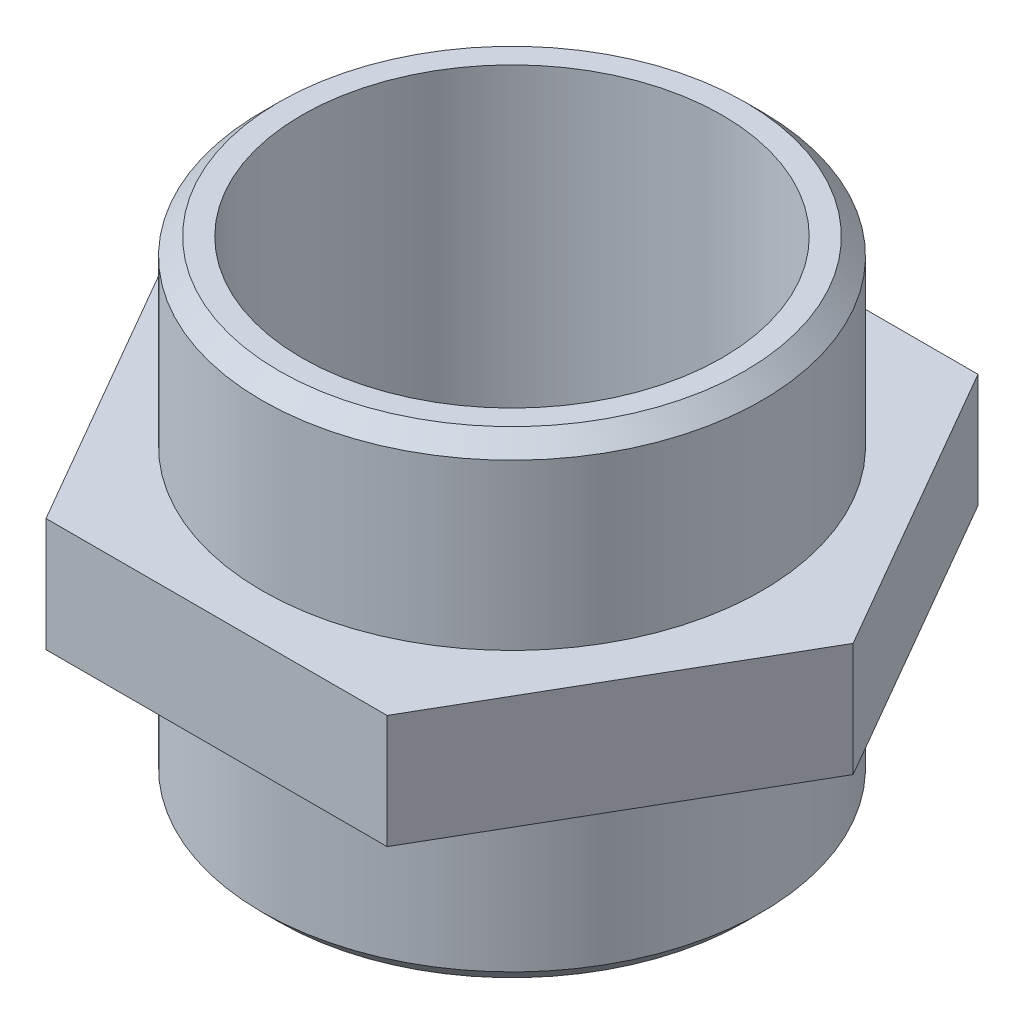
SolidWorks part; units mm, degrees
material "Brass"
ref_plane "Front Plane" through (0, 0, 0) normal (0, 0, 1) x (1, 0, 0)
ref_plane "Top Plane" through (0, 0, 0) normal (0, 1, 0) x (1, 0, 0)
ref_plane "Right Plane" through (0, 0, 0) normal (1, 0, 0) x (0, 0, -1)
sketch "Sketch1" plane through (0, 0, 0) normal (0, 1, 0) x (1, 0, 0)
  line L1 (15.0111, -26) -> (30.0222, 0)
  line L2 (30.0222, 0) -> (15.0111, 26)
  line L3 (15.0111, 26) -> (-15.0111, 26)
  line L4 (-15.0111, 26) -> (-30.0222, 0)
  line L5 (-30.0222, 0) -> (-15.0111, -26)
  line L6 (-15.0111, -26) -> (15.0111, -26)
  circle A0 centre (0, 0) radius 26 construction
  circle A1 centre (0, 0) radius 18.5
  circle A2 centre (0, 0) radius 22 construction
  dimension "D1" = 37
  dimension "D3" = 44
  dimension "D2" = 52
extrude "Boss-Extrude1" add sketch "Sketch1" along normal mid plane 10
sketch "Sketch2" plane through (0, 0, 0) normal (0, 1, 0) x (1, 0, 0)
  circle A0 centre (0, 0) radius 18.5 construction
  circle A1 centre (0, 0) radius 18.5
  circle A2 centre (0, 0) radius 22
  dimension "D1" = 44
extrude "Boss-Extrude2" add sketch "Sketch2" along normal mid plane 42
chamfer "Chamfer1" distance 1.5 angle 45 2 edges at (0, -21, 22) (0, 21, 22)
